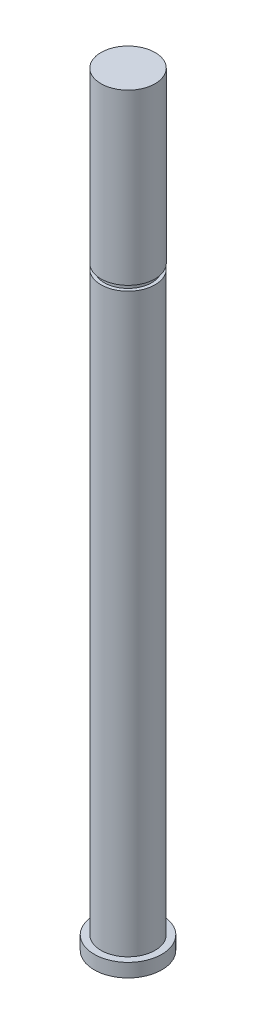
SolidWorks part; units mm, degrees
ref_plane "Front Plane" through (0, 0, 0) normal (0, 0, 1) x (1, 0, 0)
ref_plane "Top Plane" through (0, 0, 0) normal (0, 1, 0) x (1, 0, 0)
ref_plane "Right Plane" through (0, 0, 0) normal (1, 0, 0) x (0, 0, -1)
sketch "Sketch1" plane through (0, 0, 0) normal (0, 1, 0) x (1, 0, 0)
  circle A0 centre (0, 0) radius 4
  dimension "D1" = 8
extrude "Boss-Extrude1" add sketch "Sketch1" along normal blind 113
ref_plane "Plane1" through (0, 88, 0) normal (0, 1, 0) x (1, 0, 0)
sketch "Sketch2" plane through (0, 88, 0) normal (0, 1, 0) x (1, 0, 0)
  circle A0 centre (0, 0) radius 4
  circle A1 centre (0, 0) radius 3.5
extrude "Cut-Extrude1" cut sketch "Sketch2" against normal blind 0.75 contours A0 A1
sketch "Sketch3" plane through (0, 0, 0) normal (0, -1, 0) x (-1, 0, 0)
  circle A0 centre (0, 0) radius 5
extrude "Boss-Extrude2" add sketch "Sketch3" against normal blind 2
